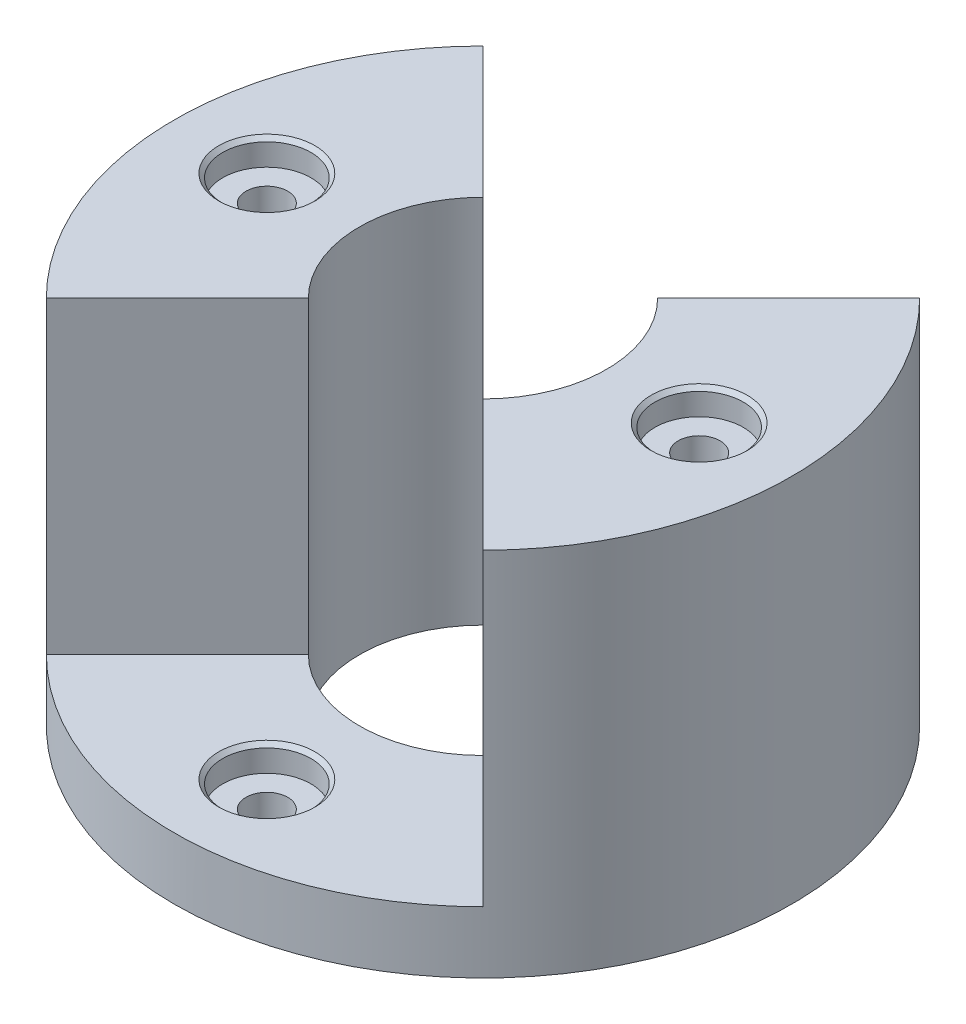
SolidWorks part; units mm, degrees
ref_plane "Alzado" through (0, 0, 0) normal (0, 0, 1) x (1, 0, 0)
ref_plane "Planta" through (0, 0, 0) normal (0, 1, 0) x (1, 0, 0)
ref_plane "Vista lateral" through (0, 0, 0) normal (1, 0, 0) x (0, 0, -1)
sketch "Croquis1" plane through (0, 0, 0) normal (0, 1, 0) x (1, 0, 0)
  circle A0 centre (0, 0) radius 50
  circle A1 centre (0, 0) radius 20
  dimension "D1" = 100
  dimension "D2" = 40
extrude "Saliente-Extruir2" add sketch "Croquis1" along normal blind 10
sketch "Croquis3" plane through (0, 0, 0) normal (0, 1, 0) x (1, 0, 0)
  line L0 (-63.2259, 0) -> (61.8949, 0) construction
  line L1 (-35.3553, 35.3553) -> (-14.1421, 14.1421)
  line L2 (-35.3553, -35.3553) -> (-14.1421, -14.1421)
  line L3 (14.1421, 14.1421) -> (35.3553, 35.3553)
  line L4 (14.1421, -14.1421) -> (35.3553, -35.3553)
  circle A0 centre (0, 0) radius 20 construction
  circle A1 centre (0, 0) radius 50 construction
  arc A2 (14.1421, -14.1421) -> (14.1421, 14.1421) centre (0, 0) ccw
  arc A3 (-35.3553, 35.3553) -> (-35.3553, -35.3553) centre (0, 0) ccw
  arc A4 (-14.1421, 14.1421) -> (-14.1421, -14.1421) centre (0, 0) ccw
  arc A5 (35.3553, -35.3553) -> (35.3553, 35.3553) centre (0, 0) ccw
  dimension "D1" = 45
  dimension "D2" = 45
extrude "Saliente-Extruir3" add sketch "Croquis3" along normal blind 60
hole_wizard "Refrentado para tornillo con cabeza troncocónica de #02" positions "Croquis14" profile "Croquis15" counterbore size "#0" standard "Ansi Inch" end condition through all
sketch "Croquis14" plane through (0, 60, 0) normal (0, 1, 0) x (1, 0, 0)
  line L0 (-66.5536, 0) -> (66.5536, 0) construction
  circle A0 centre (0, 0) radius 35 construction
  point P0 (-35, 0)
  point P2 (35, 0)
  point P14 (0, 0)
  point P15 (0, 0)
  point P16 (0, 0)
  point P17 (0, 0)
  dimension "D1" = 70
sketch "Croquis15" plane through (-35, 60, 0) normal (1, 0, 0) x (0, 0, 1)
  line L0 (0, 0) -> (0, 60)
  line L1 (0, 60) -> (3.38, 60)
  line L3 (3.38, 60) -> (3.38, 4.19)
  line L4 (7.145, 4.19) -> (3.38, 4.19)
  line L5 (7.145, 4.19) -> (7.145, 0.635)
  line L6 (7.145, 0.635) -> (7.78, 0)
  line L7 (7.78, 0) -> (0, 0)
  line L8 (-7.145, 0.635) -> (-7.78, 0) construction
  line L11 (0, -6.35) -> (0, 107.95) construction
  dimension "Diámetro de taladro hasta el siguiente" = 6.76
  dimension "Profundidad de taladro hasta el siguiente" = 60
  dimension "Diámetro de refrentado" = 14.29
  dimension "Profundidad de refrentado" = 4.19
  dimension "Diámetro de avellanado cercano" = 15.56
  dimension "Ángulo de avellanado cercano" = 90
hole_wizard "Refrentado para tornillo con cabeza troncocónica de #03" positions "Croquis16" profile "Croquis17" counterbore size "#0" standard "Ansi Inch" end condition through all
sketch "Croquis16" plane through (0, 10, 0) normal (0, 1, 0) x (1, 0, 0)
  line L0 (0, 61.2554) -> (0, -64.4255) construction
  circle A0 centre (0, 0) radius 35 construction
  point P0 (0, -35)
  point P2 (0, 35)
  point P14 (0, 0)
  point P15 (0, 0)
  point P16 (0, 0)
sketch "Croquis17" plane through (0, 10, 35) normal (1, 0, 0) x (0, 0, 1)
  line L0 (0, 0) -> (0, 10)
  line L1 (0, 10) -> (3.38, 10)
  line L3 (3.38, 10) -> (3.38, 4.19)
  line L4 (7.145, 4.19) -> (3.38, 4.19)
  line L5 (7.145, 4.19) -> (7.145, 0.635)
  line L6 (7.145, 0.635) -> (7.78, 0)
  line L7 (7.78, 0) -> (0, 0)
  line L8 (-7.145, 0.635) -> (-7.78, 0) construction
  line L11 (0, -6.35) -> (0, 107.95) construction
  dimension "Diámetro de taladro hasta el siguiente" = 6.76
  dimension "Profundidad de taladro hasta el siguiente" = 10
  dimension "Diámetro de refrentado" = 14.29
  dimension "Profundidad de refrentado" = 4.19
  dimension "Diámetro de avellanado cercano" = 15.56
  dimension "Ángulo de avellanado cercano" = 90
